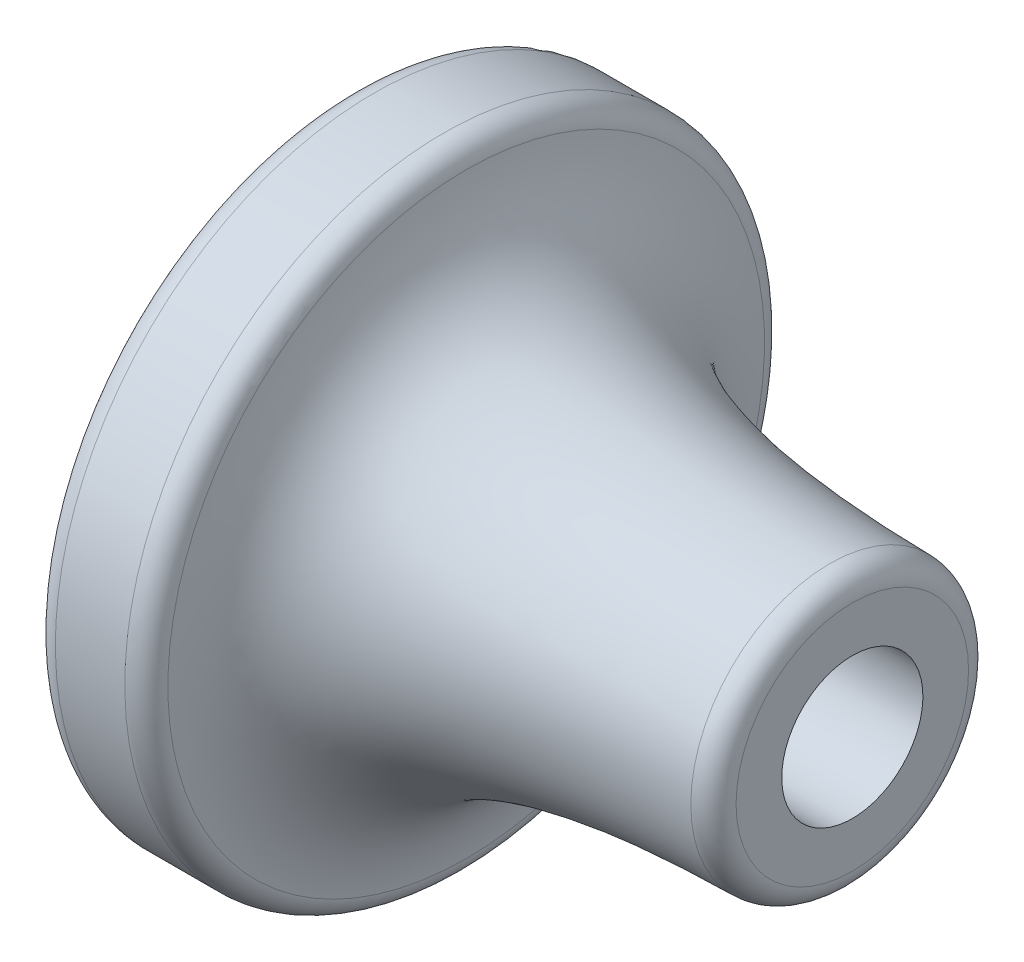
SolidWorks part; units mm, degrees
ref_plane "Front Plane" through (0, 0, 0) normal (0, 0, 1) x (1, 0, 0)
ref_plane "Top Plane" through (0, 0, 0) normal (0, 1, 0) x (1, 0, 0)
ref_plane "Right Plane" through (0, 0, 0) normal (1, 0, 0) x (0, 0, -1)
sketch "Sketch1" plane through (0, 0, 0) normal (0, 0, 1) x (1, 0, 0)
  line L0 (0, 0) -> (0, 3.1)
  line L1 (0, 3.1) -> (14, 3.1)
  line L2 (14, 3.1) -> (14, 6.1)
  line L3 (0, 0) -> (-8, 0)
  line L4 (-8, 0) -> (-8, 14)
  line L5 (-8, 14) -> (-3, 14)
  line L6 (100, 3) -> (0, 3) construction
  line L7 (-3, 14) -> (-3, 0) construction
  line L8 (14, 6.1) -> (-8, 6.1) construction
  spline S0 degree 3 poles (-3, 14) (-3, 8.8674) (0.9614, 6.1) (14, 6.1) knots 0 0 0 0 1 1 1 1
  dimension "D1" = 14
  dimension "D2" = 0.1
  dimension "D3" = 22
  dimension "D4" = 8
  dimension "D5" = 3
  dimension "D6" = 5
revolve "Revolve1" add sketch "Sketch1" angle 360 about L3
fillet "Fillet1" radius 1 3 edges at (-8, 14, 0) (-3, 14, 0) (14, 6.1, 0)
